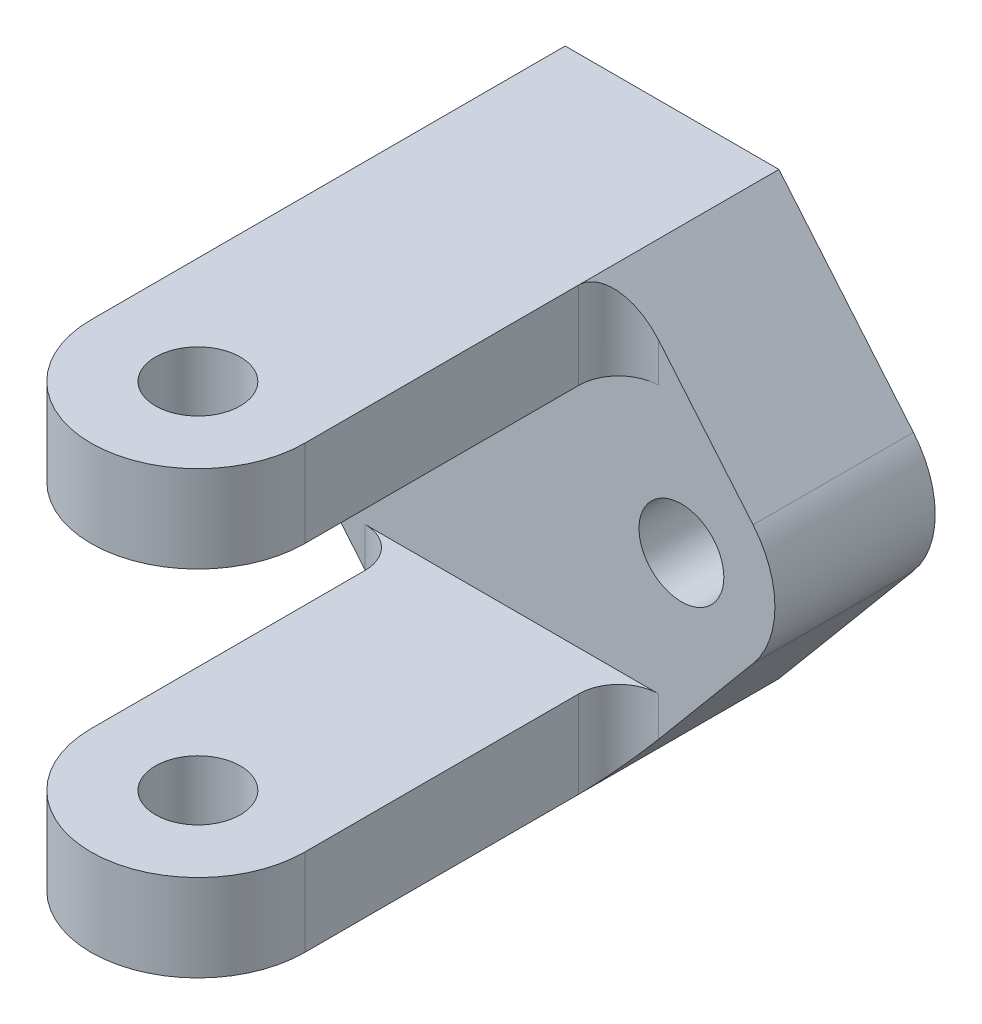
SolidWorks part; units mm, degrees
material "7075-T6 (SN)"
ref_plane "Front Plane" through (0, 0, 0) normal (0, 0, 1) x (1, 0, 0)
ref_plane "Top Plane" through (0, 0, 0) normal (0, 1, 0) x (1, 0, 0)
ref_plane "Right Plane" through (0, 0, 0) normal (1, 0, 0) x (0, 0, -1)
sketch "Sketch1" plane through (0, 0, 0) normal (0, 0, 1) x (1, 0, 0)
  line L0 (12.7, 0) -> (-12.7, 0) construction
  line L1 (-20.7, -16.51) -> (20.7, -16.51)
  line L2 (-20.7, -16.51) -> (-20.7, 16.51)
  line L3 (-20.7, 16.51) -> (20.7, 16.51)
  line L4 (20.7, -16.51) -> (20.7, 16.51)
  line L5 (-20.7, -16.51) -> (20.7, 16.51) construction
  line L6 (-20.7, 16.51) -> (20.7, -16.51) construction
  circle A0 centre (12.7, 0) radius 3.175
  circle A1 centre (-12.7, 0) radius 3.175
  point P0 (0, 0)
  dimension "D1" = 6.35
  dimension "D2" = 25.4
  dimension "D3" = 8
  dimension "D4" = 16.51
extrude "Boss-Extrude1" add sketch "Sketch1" along normal blind 12 contours L3 L4 L1 L2
sketch "Sketch2" plane through (0, 0, 12) normal (0, 0, 1) x (1, 0, 0)
  line L0 (-12.7, 0) -> (12.7, 0) construction
  line L2 (-20.7, 10) -> (20.7, 10)
  line L3 (-20.7, 10) -> (-20.7, 16.51)
  line L4 (-20.7, 16.51) -> (20.7, 16.51)
  line L5 (20.7, 10) -> (20.7, 16.51)
  line L6 (-20.7, 10) -> (20.7, 16.51) construction
  line L7 (-20.7, 16.51) -> (20.7, 10) construction
  line L8 (-20.7, 16.51) -> (-20.7, -16.51) construction
  line L9 (20.7, -10) -> (20.7, -16.51)
  line L10 (-20.7, -10) -> (-20.7, -16.51)
  line L11 (-20.7, -16.51) -> (20.7, -10) construction
  line L12 (-20.7, -10) -> (20.7, -16.51) construction
  line L13 (-20.7, -10) -> (20.7, -10)
  line L14 (-20.7, -16.51) -> (20.7, -16.51)
  circle A0 centre (-12.7, 0) radius 3.175 construction
  circle A1 centre (12.7, 0) radius 3.175 construction
  point P6 (0, 13.255)
  point P21 (0, -13.255)
  dimension "D1" = 20
extrude "Boss-Extrude2" add sketch "Sketch2" along normal blind 53
sketch "Sketch3" plane through (0, 0, 0) normal (0, 1, 0) x (1, 0, 0)
  point P0 (0, -35.5)
  dimension "D1" = 35.5
ref_point "UBJ Point"
sketch "Sketch4" plane through (0, 0, 0) normal (0, 1, 0) x (1, 0, 0)
  circle A0 centre (0, -35.5) radius 3.175
  dimension "D1" = 6.35
extrude "Cut-Extrude1" cut sketch "Sketch4" against normal up to surface and the other way up to surface up to face at (0, -16.51, 32.5) other way up to face at (0, 16.51, 32.5)
sketch "Sketch5" plane through (0, 0, 0) normal (0, 1, 0) x (1, 0, 0)
  line L0 (20.7, -12) -> (8.3595, -39.2814)
  line L1 (-8.3595, -39.2814) -> (-20.7, -12)
  line L4 (20.7, 0) -> (-20.7, 0)
  line L5 (-20.7, 0) -> (-20.7, -65)
  line L6 (-20.7, -65) -> (20.7, -65)
  line L7 (20.7, -65) -> (20.7, 0)
  line L9 (-20.7, -12) -> (-20.7, -65)
  line L10 (-20.7, -65) -> (20.7, -65)
  line L11 (20.7, -65) -> (20.7, -12)
  line L12 (20.7, -12) -> (-20.7, -12)
  line L13 (20.7, -65) -> (20.7, -12)
  line L14 (-20.7, -65) -> (20.7, -65)
  line L15 (-20.7, -12) -> (-20.7, -65)
  line L17 (20.7, -65) -> (20.7, -12)
  line L18 (-20.7, -65) -> (20.7, -65)
  line L19 (-20.7, -12) -> (-20.7, -65)
  arc A0 (-8.3595, -39.2814) -> (8.3595, -39.2814) centre (0, -35.5) ccw
  circle A1 centre (0, -35.5) radius 3.175 construction
  circle A2 centre (0, -35.5) radius 3.175 construction
  dimension "D3" = 6
  dimension "D1" = 0
  dimension "D2" = 0
extrude "Cut-Extrude2" [suppressed] cut sketch "Sketch5" against normal up to surface and the other way up to surface contours A0 L1 L9 L10 L11 L0
sketch "Sketch6" plane through (0, 0, 0) normal (0, 1, 0) x (1, 0, 0)
  line L0 (-8, -35.5) -> (-8, -20)
  line L1 (8, -35.5) -> (8, -20)
  line L2 (-16, -12) -> (-20.7, -12)
  line L3 (-8, -20) -> (-8, -12)
  line L4 (20.7, -12) -> (-20.7, -12)
  line L5 (-20.7, -12) -> (-20.7, -65)
  line L6 (-20.7, -65) -> (20.7, -65)
  line L7 (20.7, -65) -> (20.7, -12)
  line L8 (20.7, -12) -> (16, -12)
  line L9 (-20.7, -12) -> (-20.7, -65)
  line L10 (-20.7, -65) -> (20.7, -65)
  line L11 (20.7, -65) -> (20.7, -12)
  line L12 (-8, -12) -> (-16, -12)
  line L13 (8, -20) -> (8, -12)
  line L14 (8, -12) -> (16, -12)
  arc A0 (-8, -35.5) -> (8, -35.5) centre (0, -35.5) ccw
  circle A1 centre (0, -35.5) radius 3.175 construction
  arc A2 (-8, -20) -> (-16, -12) centre (-16, -20) ccw construction
  arc A3 (8, -20) -> (16, -12) centre (16, -20) cw construction
  dimension "D2" = 8
  dimension "D3" = 8
  dimension "D1" = 0
extrude "Cut-Extrude3" cut sketch "Sketch6" against normal up to surface and the other way up to surface up to face at (0, -16.51, 38.675) other way up to face at (0, 16.51, 32.325)
fillet "Fillet1" [suppressed] radius 12.7
sketch "Sketch7" plane through (0, 0, 0) normal (0, 0, 1) x (1, 0, 0)
  line L0 (-12.7, 7) -> (-8, 7)
  line L1 (-12.7, -7) -> (-8, -7)
  line L2 (-8, 16.51) -> (-8, 7)
  line L3 (-8, -16.51) -> (-8, -7)
  line L4 (0, 10.3988) -> (0, -8.4154) construction
  line L5 (8, -16.51) -> (8, -7)
  line L6 (20.7, -16.51) -> (8, -16.51)
  line L7 (20.7, 16.51) -> (20.7, -16.51)
  line L8 (8, 16.51) -> (20.7, 16.51)
  line L9 (8, 16.51) -> (8, 7)
  line L10 (12.7, 7) -> (8, 7)
  line L11 (12.7, -7) -> (8, -7)
  line L12 (8, 10) -> (-8, 10)
  line L13 (-8, 10) -> (-8, 16.51)
  line L14 (-8, 16.51) -> (-20.7, 16.51)
  line L15 (-20.7, 16.51) -> (-20.7, -16.51)
  line L16 (-20.7, -16.51) -> (-8, -16.51)
  line L17 (-8, -16.51) -> (-8, -10)
  line L18 (-8, -10) -> (8, -10)
  line L19 (8, -10) -> (8, -16.51)
  line L20 (8, -16.51) -> (20.7, -16.51)
  line L21 (20.7, -16.51) -> (20.7, 16.51)
  line L22 (20.7, 16.51) -> (8, 16.51)
  line L23 (8, 16.51) -> (8, 10)
  line L26 (-8, 16.51) -> (-20.7, 16.51)
  line L27 (-20.7, 16.51) -> (-20.7, -16.51)
  line L28 (-20.7, -16.51) -> (-8, -16.51)
  line L32 (8, -16.51) -> (20.7, -16.51)
  line L33 (20.7, -16.51) -> (20.7, 16.51)
  line L34 (20.7, 16.51) -> (8, 16.51)
  line L36 (-8, 10) -> (8, 10) construction
  line L37 (8, -10) -> (-8, -10) construction
  line L38 (-8, 10) -> (8, 10)
  line L39 (8, -10) -> (-8, -10)
  arc A0 (-12.7, 7) -> (-12.7, -7) centre (-12.7, 0) ccw
  circle A1 centre (-12.7, 0) radius 3.175 construction
  arc A2 (12.7, 7) -> (12.7, -7) centre (12.7, 0) cw
  dimension "D2" = 7
  dimension "D1" = 0
extrude "Cut-Extrude4" cut sketch "Sketch7" along normal up to surface (12 mm away) contours A0 L0 L2 L26 L27 L28 L3 L1 | L10 A2 L11 L5 L6 L7 L8 L9 up to face at (0, 0, 12)
fillet "Fillet2" [suppressed] radius 5
sketch "Sketch8" plane through (0, 0, 0) normal (0, 0, 1) x (1, 0, 0)
  line L0 (12.7, 7) -> (8, 7) construction
  line L1 (8, 16.51) -> (8, 7) construction
  line L2 (12.7, 7) -> (8, 7)
  line L3 (8, 16.51) -> (8, 7)
  line L4 (6.7586, 0) -> (-5.803, 0) construction
  line L5 (0, 7.1591) -> (0, -7.1591) construction
  line L6 (8, 16.51) -> (18.0658, 4.4954)
  line L7 (-8, 16.51) -> (-8, 7)
  line L8 (-12.7, 7) -> (-8, 7)
  line L9 (-8, 16.51) -> (-18.0658, 4.4954)
  line L10 (-8, -16.51) -> (-18.0658, -4.4954)
  line L11 (-12.7, -7) -> (-8, -7)
  line L12 (-8, -16.51) -> (-8, -7)
  line L13 (8, -16.51) -> (8, -7)
  line L14 (12.7, -7) -> (8, -7)
  line L15 (8, -16.51) -> (18.0658, -4.4954)
  arc A0 (12.7, -7) -> (12.7, 7) centre (12.7, 0) ccw construction
  arc A1 (18.0658, 4.4954) -> (12.7, 7) centre (12.7, 0) ccw
  arc A2 (-18.0658, 4.4954) -> (-12.7, 7) centre (-12.7, 0) cw
  arc A3 (-18.0658, -4.4954) -> (-12.7, -7) centre (-12.7, 0) ccw
  arc A4 (18.0658, -4.4954) -> (12.7, -7) centre (12.7, 0) cw
extrude "Boss-Extrude3" add sketch "Sketch8" along normal up to surface (12 mm away) contours L15 A4 L14 L13 | A3 L10 L12 L11 | L6 A1 L2 L3 | L9 A2 L8 L7 up to face at (-9.525, 0, 12)
fillet "Fillet3" radius 3 4 edges at (8, 13.255, 12) (-8, 13.255, 12) (-8, -13.255, 12) (8, -13.255, 12)
